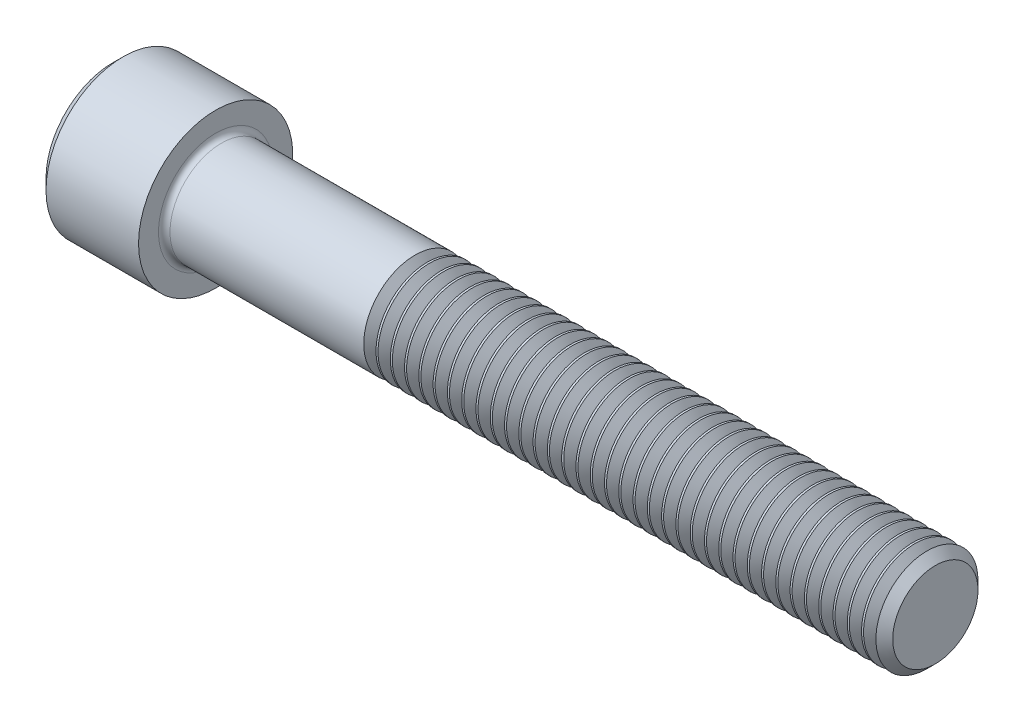
SolidWorks part; units mm, degrees
material "AISI 1020 Steel, Cold Rolled"
ref_plane "Front Plane" through (0, 0, 0) normal (0, 0, 1) x (1, 0, 0)
ref_plane "Top Plane" through (0, 0, 0) normal (0, 1, 0) x (1, 0, 0)
ref_plane "Right Plane" through (0, 0, 0) normal (1, 0, 0) x (0, 0, -1)
ref_plane "Plane1" through (0, 0, 0) normal (0, 0, -1) x (-1, 0, 0)
sketch "Sketch1" plane through (0, 0, 0) normal (0, 0, -1) x (-1, 0, 0)
  line L0 (-6.35, 4.7625) -> (-6.35, 0)
  line L1 (-6.35, 0) -> (0, 0)
  line L2 (0, 0) -> (0, 4.7625)
  line L3 (0, 4.7625) -> (-6.35, 4.7625)
  line L4 (-6.35, 0) -> (0, 0) construction
revolve "Revolve1" add sketch "Sketch1" angle 360 about L4
sketch "Sketch2" plane through (6.35, 0, 0) normal (1, 0, 0) x (0, 0, -1)
  circle A0 centre (0, 0) radius 3.175
extrude "Boss-Extrude1" add sketch "Sketch2" along normal blind 12.3212
sketch "Sketch3" plane through (18.6712, 0, 0) normal (1, 0, 0) x (0, 0, -1)
  circle A0 centre (0, 0) radius 3.175
extrude "Boss-Extrude2" add sketch "Sketch3" along normal blind 0.3788 draft 55
sketch "Sketch4" plane through (19.05, 0, 0) normal (1, 0, 0) x (0, 0, -1)
  circle A0 centre (0, 0) radius 2.634
extrude "Boss-Extrude3" add sketch "Sketch4" along normal blind 0.3788 draft 55 draft outward yes
sketch "Sketch5" plane through (19.4288, 0, 0) normal (1, 0, 0) x (0, 0, -1)
  circle A0 centre (0, 0) radius 3.175
extrude "Boss-Extrude4" add sketch "Sketch5" along normal blind 0.1243
sketch "Sketch6" plane through (19.5531, 0, 0) normal (1, 0, 0) x (0, 0, -1)
  circle A0 centre (0, 0) radius 3.175
extrude "Boss-Extrude5" add sketch "Sketch6" along normal blind 0.3788 draft 55
sketch "Sketch7" plane through (19.9319, 0, 0) normal (1, 0, 0) x (0, 0, -1)
  circle A0 centre (0, 0) radius 2.634
extrude "Boss-Extrude6" add sketch "Sketch7" along normal blind 0.3788 draft 55 draft outward yes
sketch "Sketch8" plane through (20.3108, 0, 0) normal (1, 0, 0) x (0, 0, -1)
  circle A0 centre (0, 0) radius 3.175
extrude "Boss-Extrude7" add sketch "Sketch8" along normal blind 0.1243
sketch "Sketch9" plane through (20.4351, 0, 0) normal (1, 0, 0) x (0, 0, -1)
  circle A0 centre (0, 0) radius 3.175
extrude "Boss-Extrude8" add sketch "Sketch9" along normal blind 0.3788 draft 55
sketch "Sketch10" plane through (20.8139, 0, 0) normal (1, 0, 0) x (0, 0, -1)
  circle A0 centre (0, 0) radius 2.634
extrude "Boss-Extrude9" add sketch "Sketch10" along normal blind 0.3788 draft 55 draft outward yes
sketch "Sketch11" plane through (21.1927, 0, 0) normal (1, 0, 0) x (0, 0, -1)
  circle A0 centre (0, 0) radius 3.175
extrude "Boss-Extrude10" add sketch "Sketch11" along normal blind 0.1243
sketch "Sketch12" plane through (21.317, 0, 0) normal (1, 0, 0) x (0, 0, -1)
  circle A0 centre (0, 0) radius 3.175
extrude "Boss-Extrude11" add sketch "Sketch12" along normal blind 0.3788 draft 55
sketch "Sketch13" plane through (21.6958, 0, 0) normal (1, 0, 0) x (0, 0, -1)
  circle A0 centre (0, 0) radius 2.634
extrude "Boss-Extrude12" add sketch "Sketch13" along normal blind 0.3788 draft 55 draft outward yes
sketch "Sketch14" plane through (22.0747, 0, 0) normal (1, 0, 0) x (0, 0, -1)
  circle A0 centre (0, 0) radius 3.175
extrude "Boss-Extrude13" add sketch "Sketch14" along normal blind 0.1243
sketch "Sketch15" plane through (22.199, 0, 0) normal (1, 0, 0) x (0, 0, -1)
  circle A0 centre (0, 0) radius 3.175
extrude "Boss-Extrude14" add sketch "Sketch15" along normal blind 0.3788 draft 55
sketch "Sketch16" plane through (22.5778, 0, 0) normal (1, 0, 0) x (0, 0, -1)
  circle A0 centre (0, 0) radius 2.634
extrude "Boss-Extrude15" add sketch "Sketch16" along normal blind 0.3788 draft 55 draft outward yes
sketch "Sketch17" plane through (22.9566, 0, 0) normal (1, 0, 0) x (0, 0, -1)
  circle A0 centre (0, 0) radius 3.175
extrude "Boss-Extrude16" add sketch "Sketch17" along normal blind 0.1243
sketch "Sketch18" plane through (23.0809, 0, 0) normal (1, 0, 0) x (0, 0, -1)
  circle A0 centre (0, 0) radius 3.175
extrude "Boss-Extrude17" add sketch "Sketch18" along normal blind 0.3788 draft 55
sketch "Sketch19" plane through (23.4597, 0, 0) normal (1, 0, 0) x (0, 0, -1)
  circle A0 centre (0, 0) radius 2.634
extrude "Boss-Extrude18" add sketch "Sketch19" along normal blind 0.3788 draft 55 draft outward yes
sketch "Sketch20" plane through (23.8385, 0, 0) normal (1, 0, 0) x (0, 0, -1)
  circle A0 centre (0, 0) radius 3.175
extrude "Boss-Extrude19" add sketch "Sketch20" along normal blind 0.1243
sketch "Sketch21" plane through (23.9628, 0, 0) normal (1, 0, 0) x (0, 0, -1)
  circle A0 centre (0, 0) radius 3.175
extrude "Boss-Extrude20" add sketch "Sketch21" along normal blind 0.3788 draft 55
sketch "Sketch22" plane through (24.3417, 0, 0) normal (1, 0, 0) x (0, 0, -1)
  circle A0 centre (0, 0) radius 2.634
extrude "Boss-Extrude21" add sketch "Sketch22" along normal blind 0.3788 draft 55 draft outward yes
sketch "Sketch23" plane through (24.7205, 0, 0) normal (1, 0, 0) x (0, 0, -1)
  circle A0 centre (0, 0) radius 3.175
extrude "Boss-Extrude22" add sketch "Sketch23" along normal blind 0.1243
sketch "Sketch24" plane through (24.8448, 0, 0) normal (1, 0, 0) x (0, 0, -1)
  circle A0 centre (0, 0) radius 3.175
extrude "Boss-Extrude23" add sketch "Sketch24" along normal blind 0.3788 draft 55
sketch "Sketch25" plane through (25.2236, 0, 0) normal (1, 0, 0) x (0, 0, -1)
  circle A0 centre (0, 0) radius 2.634
extrude "Boss-Extrude24" add sketch "Sketch25" along normal blind 0.3788 draft 55 draft outward yes
sketch "Sketch26" plane through (25.6024, 0, 0) normal (1, 0, 0) x (0, 0, -1)
  circle A0 centre (0, 0) radius 3.175
extrude "Boss-Extrude25" add sketch "Sketch26" along normal blind 0.1243
sketch "Sketch27" plane through (25.7267, 0, 0) normal (1, 0, 0) x (0, 0, -1)
  circle A0 centre (0, 0) radius 3.175
extrude "Boss-Extrude26" add sketch "Sketch27" along normal blind 0.3788 draft 55
sketch "Sketch28" plane through (26.1056, 0, 0) normal (1, 0, 0) x (0, 0, -1)
  circle A0 centre (0, 0) radius 2.634
extrude "Boss-Extrude27" add sketch "Sketch28" along normal blind 0.3788 draft 55 draft outward yes
sketch "Sketch29" plane through (26.4844, 0, 0) normal (1, 0, 0) x (0, 0, -1)
  circle A0 centre (0, 0) radius 3.175
extrude "Boss-Extrude28" add sketch "Sketch29" along normal blind 0.1243
sketch "Sketch30" plane through (26.6087, 0, 0) normal (1, 0, 0) x (0, 0, -1)
  circle A0 centre (0, 0) radius 3.175
extrude "Boss-Extrude29" add sketch "Sketch30" along normal blind 0.3788 draft 55
sketch "Sketch31" plane through (26.9875, 0, 0) normal (1, 0, 0) x (0, 0, -1)
  circle A0 centre (0, 0) radius 2.634
extrude "Boss-Extrude30" add sketch "Sketch31" along normal blind 0.3788 draft 55 draft outward yes
sketch "Sketch32" plane through (27.3663, 0, 0) normal (1, 0, 0) x (0, 0, -1)
  circle A0 centre (0, 0) radius 3.175
extrude "Boss-Extrude31" add sketch "Sketch32" along normal blind 0.1243
sketch "Sketch33" plane through (27.4906, 0, 0) normal (1, 0, 0) x (0, 0, -1)
  circle A0 centre (0, 0) radius 3.175
extrude "Boss-Extrude32" add sketch "Sketch33" along normal blind 0.3788 draft 55
sketch "Sketch34" plane through (27.8694, 0, 0) normal (1, 0, 0) x (0, 0, -1)
  circle A0 centre (0, 0) radius 2.634
extrude "Boss-Extrude33" add sketch "Sketch34" along normal blind 0.3788 draft 55 draft outward yes
sketch "Sketch35" plane through (28.2483, 0, 0) normal (1, 0, 0) x (0, 0, -1)
  circle A0 centre (0, 0) radius 3.175
extrude "Boss-Extrude34" add sketch "Sketch35" along normal blind 0.1243
sketch "Sketch36" plane through (28.3726, 0, 0) normal (1, 0, 0) x (0, 0, -1)
  circle A0 centre (0, 0) radius 3.175
extrude "Boss-Extrude35" add sketch "Sketch36" along normal blind 0.3788 draft 55
sketch "Sketch37" plane through (28.7514, 0, 0) normal (1, 0, 0) x (0, 0, -1)
  circle A0 centre (0, 0) radius 2.634
extrude "Boss-Extrude36" add sketch "Sketch37" along normal blind 0.3788 draft 55 draft outward yes
sketch "Sketch38" plane through (29.1302, 0, 0) normal (1, 0, 0) x (0, 0, -1)
  circle A0 centre (0, 0) radius 3.175
extrude "Boss-Extrude37" add sketch "Sketch38" along normal blind 0.1243
sketch "Sketch39" plane through (29.2545, 0, 0) normal (1, 0, 0) x (0, 0, -1)
  circle A0 centre (0, 0) radius 3.175
extrude "Boss-Extrude38" add sketch "Sketch39" along normal blind 0.3788 draft 55
sketch "Sketch40" plane through (29.6333, 0, 0) normal (1, 0, 0) x (0, 0, -1)
  circle A0 centre (0, 0) radius 2.634
extrude "Boss-Extrude39" add sketch "Sketch40" along normal blind 0.3788 draft 55 draft outward yes
sketch "Sketch41" plane through (30.0122, 0, 0) normal (1, 0, 0) x (0, 0, -1)
  circle A0 centre (0, 0) radius 3.175
extrude "Boss-Extrude40" add sketch "Sketch41" along normal blind 0.1243
sketch "Sketch42" plane through (30.1365, 0, 0) normal (1, 0, 0) x (0, 0, -1)
  circle A0 centre (0, 0) radius 3.175
extrude "Boss-Extrude41" add sketch "Sketch42" along normal blind 0.3788 draft 55
sketch "Sketch43" plane through (30.5153, 0, 0) normal (1, 0, 0) x (0, 0, -1)
  circle A0 centre (0, 0) radius 2.634
extrude "Boss-Extrude42" add sketch "Sketch43" along normal blind 0.3788 draft 55 draft outward yes
sketch "Sketch44" plane through (30.8941, 0, 0) normal (1, 0, 0) x (0, 0, -1)
  circle A0 centre (0, 0) radius 3.175
extrude "Boss-Extrude43" add sketch "Sketch44" along normal blind 0.1243
sketch "Sketch45" plane through (31.0184, 0, 0) normal (1, 0, 0) x (0, 0, -1)
  circle A0 centre (0, 0) radius 3.175
extrude "Boss-Extrude44" add sketch "Sketch45" along normal blind 0.3788 draft 55
sketch "Sketch46" plane through (31.3972, 0, 0) normal (1, 0, 0) x (0, 0, -1)
  circle A0 centre (0, 0) radius 2.634
extrude "Boss-Extrude45" add sketch "Sketch46" along normal blind 0.3788 draft 55 draft outward yes
sketch "Sketch47" plane through (31.776, 0, 0) normal (1, 0, 0) x (0, 0, -1)
  circle A0 centre (0, 0) radius 3.175
extrude "Boss-Extrude46" add sketch "Sketch47" along normal blind 0.1243
sketch "Sketch48" plane through (31.9003, 0, 0) normal (1, 0, 0) x (0, 0, -1)
  circle A0 centre (0, 0) radius 3.175
extrude "Boss-Extrude47" add sketch "Sketch48" along normal blind 0.3788 draft 55
sketch "Sketch49" plane through (32.2792, 0, 0) normal (1, 0, 0) x (0, 0, -1)
  circle A0 centre (0, 0) radius 2.634
extrude "Boss-Extrude48" add sketch "Sketch49" along normal blind 0.3788 draft 55 draft outward yes
sketch "Sketch50" plane through (32.658, 0, 0) normal (1, 0, 0) x (0, 0, -1)
  circle A0 centre (0, 0) radius 3.175
extrude "Boss-Extrude49" add sketch "Sketch50" along normal blind 0.1243
sketch "Sketch51" plane through (32.7823, 0, 0) normal (1, 0, 0) x (0, 0, -1)
  circle A0 centre (0, 0) radius 3.175
extrude "Boss-Extrude50" add sketch "Sketch51" along normal blind 0.3788 draft 55
sketch "Sketch52" plane through (33.1611, 0, 0) normal (1, 0, 0) x (0, 0, -1)
  circle A0 centre (0, 0) radius 2.634
extrude "Boss-Extrude51" add sketch "Sketch52" along normal blind 0.3788 draft 55 draft outward yes
sketch "Sketch53" plane through (33.5399, 0, 0) normal (1, 0, 0) x (0, 0, -1)
  circle A0 centre (0, 0) radius 3.175
extrude "Boss-Extrude52" add sketch "Sketch53" along normal blind 0.1243
sketch "Sketch54" plane through (33.6642, 0, 0) normal (1, 0, 0) x (0, 0, -1)
  circle A0 centre (0, 0) radius 3.175
extrude "Boss-Extrude53" add sketch "Sketch54" along normal blind 0.3788 draft 55
sketch "Sketch55" plane through (34.0431, 0, 0) normal (1, 0, 0) x (0, 0, -1)
  circle A0 centre (0, 0) radius 2.634
extrude "Boss-Extrude54" add sketch "Sketch55" along normal blind 0.3788 draft 55 draft outward yes
sketch "Sketch56" plane through (34.4219, 0, 0) normal (1, 0, 0) x (0, 0, -1)
  circle A0 centre (0, 0) radius 3.175
extrude "Boss-Extrude55" add sketch "Sketch56" along normal blind 0.1243
sketch "Sketch57" plane through (34.5462, 0, 0) normal (1, 0, 0) x (0, 0, -1)
  circle A0 centre (0, 0) radius 3.175
extrude "Boss-Extrude56" add sketch "Sketch57" along normal blind 0.3788 draft 55
sketch "Sketch58" plane through (34.925, 0, 0) normal (1, 0, 0) x (0, 0, -1)
  circle A0 centre (0, 0) radius 2.634
extrude "Boss-Extrude57" add sketch "Sketch58" along normal blind 0.3788 draft 55 draft outward yes
sketch "Sketch59" plane through (35.3038, 0, 0) normal (1, 0, 0) x (0, 0, -1)
  circle A0 centre (0, 0) radius 3.175
extrude "Boss-Extrude58" add sketch "Sketch59" along normal blind 0.1243
sketch "Sketch60" plane through (35.4281, 0, 0) normal (1, 0, 0) x (0, 0, -1)
  circle A0 centre (0, 0) radius 3.175
extrude "Boss-Extrude59" add sketch "Sketch60" along normal blind 0.3788 draft 55
sketch "Sketch61" plane through (35.8069, 0, 0) normal (1, 0, 0) x (0, 0, -1)
  circle A0 centre (0, 0) radius 2.634
extrude "Boss-Extrude60" add sketch "Sketch61" along normal blind 0.3788 draft 55 draft outward yes
sketch "Sketch62" plane through (36.1858, 0, 0) normal (1, 0, 0) x (0, 0, -1)
  circle A0 centre (0, 0) radius 3.175
extrude "Boss-Extrude61" add sketch "Sketch62" along normal blind 0.1243
sketch "Sketch63" plane through (36.3101, 0, 0) normal (1, 0, 0) x (0, 0, -1)
  circle A0 centre (0, 0) radius 3.175
extrude "Boss-Extrude62" add sketch "Sketch63" along normal blind 0.3788 draft 55
sketch "Sketch64" plane through (36.6889, 0, 0) normal (1, 0, 0) x (0, 0, -1)
  circle A0 centre (0, 0) radius 2.634
extrude "Boss-Extrude63" add sketch "Sketch64" along normal blind 0.3788 draft 55 draft outward yes
sketch "Sketch65" plane through (37.0677, 0, 0) normal (1, 0, 0) x (0, 0, -1)
  circle A0 centre (0, 0) radius 3.175
extrude "Boss-Extrude64" add sketch "Sketch65" along normal blind 0.1243
sketch "Sketch66" plane through (37.192, 0, 0) normal (1, 0, 0) x (0, 0, -1)
  circle A0 centre (0, 0) radius 3.175
extrude "Boss-Extrude65" add sketch "Sketch66" along normal blind 0.3788 draft 55
sketch "Sketch67" plane through (37.5708, 0, 0) normal (1, 0, 0) x (0, 0, -1)
  circle A0 centre (0, 0) radius 2.634
extrude "Boss-Extrude66" add sketch "Sketch67" along normal blind 0.3788 draft 55 draft outward yes
sketch "Sketch68" plane through (37.9497, 0, 0) normal (1, 0, 0) x (0, 0, -1)
  circle A0 centre (0, 0) radius 3.175
extrude "Boss-Extrude67" add sketch "Sketch68" along normal blind 0.1243
sketch "Sketch69" plane through (38.074, 0, 0) normal (1, 0, 0) x (0, 0, -1)
  circle A0 centre (0, 0) radius 3.175
extrude "Boss-Extrude68" add sketch "Sketch69" along normal blind 0.3788 draft 55
sketch "Sketch70" plane through (38.4528, 0, 0) normal (1, 0, 0) x (0, 0, -1)
  circle A0 centre (0, 0) radius 2.634
extrude "Boss-Extrude69" add sketch "Sketch70" along normal blind 0.3788 draft 55 draft outward yes
sketch "Sketch71" plane through (38.8316, 0, 0) normal (1, 0, 0) x (0, 0, -1)
  circle A0 centre (0, 0) radius 3.175
extrude "Boss-Extrude70" add sketch "Sketch71" along normal blind 0.1243
sketch "Sketch72" plane through (38.9559, 0, 0) normal (1, 0, 0) x (0, 0, -1)
  circle A0 centre (0, 0) radius 3.175
extrude "Boss-Extrude71" add sketch "Sketch72" along normal blind 0.3788 draft 55
sketch "Sketch73" plane through (39.3347, 0, 0) normal (1, 0, 0) x (0, 0, -1)
  circle A0 centre (0, 0) radius 2.634
extrude "Boss-Extrude72" add sketch "Sketch73" along normal blind 0.3788 draft 55 draft outward yes
sketch "Sketch74" plane through (39.7135, 0, 0) normal (1, 0, 0) x (0, 0, -1)
  circle A0 centre (0, 0) radius 3.175
extrude "Boss-Extrude73" add sketch "Sketch74" along normal blind 0.1243
sketch "Sketch75" plane through (39.8378, 0, 0) normal (1, 0, 0) x (0, 0, -1)
  circle A0 centre (0, 0) radius 3.175
extrude "Boss-Extrude74" add sketch "Sketch75" along normal blind 0.3788 draft 55
sketch "Sketch76" plane through (40.2167, 0, 0) normal (1, 0, 0) x (0, 0, -1)
  circle A0 centre (0, 0) radius 2.634
extrude "Boss-Extrude75" add sketch "Sketch76" along normal blind 0.3788 draft 55 draft outward yes
sketch "Sketch77" plane through (40.5955, 0, 0) normal (1, 0, 0) x (0, 0, -1)
  circle A0 centre (0, 0) radius 3.175
extrude "Boss-Extrude76" add sketch "Sketch77" along normal blind 0.1243
sketch "Sketch78" plane through (40.7198, 0, 0) normal (1, 0, 0) x (0, 0, -1)
  circle A0 centre (0, 0) radius 3.175
extrude "Boss-Extrude77" add sketch "Sketch78" along normal blind 0.3788 draft 55
sketch "Sketch79" plane through (41.0986, 0, 0) normal (1, 0, 0) x (0, 0, -1)
  circle A0 centre (0, 0) radius 2.634
extrude "Boss-Extrude78" add sketch "Sketch79" along normal blind 0.3788 draft 55 draft outward yes
sketch "Sketch80" plane through (41.4774, 0, 0) normal (1, 0, 0) x (0, 0, -1)
  circle A0 centre (0, 0) radius 3.175
extrude "Boss-Extrude79" add sketch "Sketch80" along normal blind 0.1243
sketch "Sketch81" plane through (41.6017, 0, 0) normal (1, 0, 0) x (0, 0, -1)
  circle A0 centre (0, 0) radius 3.175
extrude "Boss-Extrude80" add sketch "Sketch81" along normal blind 0.3788 draft 55
sketch "Sketch82" plane through (41.9806, 0, 0) normal (1, 0, 0) x (0, 0, -1)
  circle A0 centre (0, 0) radius 2.634
extrude "Boss-Extrude81" add sketch "Sketch82" along normal blind 0.3788 draft 55 draft outward yes
sketch "Sketch83" plane through (42.3594, 0, 0) normal (1, 0, 0) x (0, 0, -1)
  circle A0 centre (0, 0) radius 3.175
extrude "Boss-Extrude82" add sketch "Sketch83" along normal blind 0.1243
sketch "Sketch84" plane through (42.4837, 0, 0) normal (1, 0, 0) x (0, 0, -1)
  circle A0 centre (0, 0) radius 3.175
extrude "Boss-Extrude83" add sketch "Sketch84" along normal blind 0.3788 draft 55
sketch "Sketch85" plane through (42.8625, 0, 0) normal (1, 0, 0) x (0, 0, -1)
  circle A0 centre (0, 0) radius 2.634
extrude "Boss-Extrude84" add sketch "Sketch85" along normal blind 0.3788 draft 55 draft outward yes
sketch "Sketch86" plane through (43.2413, 0, 0) normal (1, 0, 0) x (0, 0, -1)
  circle A0 centre (0, 0) radius 3.175
extrude "Boss-Extrude85" add sketch "Sketch86" along normal blind 0.1243
sketch "Sketch87" plane through (43.3656, 0, 0) normal (1, 0, 0) x (0, 0, -1)
  circle A0 centre (0, 0) radius 3.175
extrude "Boss-Extrude86" add sketch "Sketch87" along normal blind 0.3788 draft 55
sketch "Sketch88" plane through (43.7444, 0, 0) normal (1, 0, 0) x (0, 0, -1)
  circle A0 centre (0, 0) radius 2.634
extrude "Boss-Extrude87" add sketch "Sketch88" along normal blind 0.3788 draft 55 draft outward yes
sketch "Sketch89" plane through (44.1233, 0, 0) normal (1, 0, 0) x (0, 0, -1)
  circle A0 centre (0, 0) radius 3.175
extrude "Boss-Extrude88" add sketch "Sketch89" along normal blind 0.1243
sketch "Sketch90" plane through (44.2476, 0, 0) normal (1, 0, 0) x (0, 0, -1)
  circle A0 centre (0, 0) radius 3.175
extrude "Boss-Extrude89" add sketch "Sketch90" along normal blind 0.3788 draft 55
sketch "Sketch91" plane through (44.6264, 0, 0) normal (1, 0, 0) x (0, 0, -1)
  circle A0 centre (0, 0) radius 2.634
extrude "Boss-Extrude90" add sketch "Sketch91" along normal blind 0.3788 draft 55 draft outward yes
sketch "Sketch92" plane through (45.0052, 0, 0) normal (1, 0, 0) x (0, 0, -1)
  circle A0 centre (0, 0) radius 3.175
extrude "Boss-Extrude91" add sketch "Sketch92" along normal blind 0.1243
sketch "Sketch93" plane through (45.1295, 0, 0) normal (1, 0, 0) x (0, 0, -1)
  circle A0 centre (0, 0) radius 3.175
extrude "Boss-Extrude92" add sketch "Sketch93" along normal blind 0.3788 draft 55
sketch "Sketch94" plane through (45.5083, 0, 0) normal (1, 0, 0) x (0, 0, -1)
  circle A0 centre (0, 0) radius 2.634
extrude "Boss-Extrude93" add sketch "Sketch94" along normal blind 0.3788 draft 55 draft outward yes
sketch "Sketch95" plane through (45.8872, 0, 0) normal (1, 0, 0) x (0, 0, -1)
  circle A0 centre (0, 0) radius 3.175
extrude "Boss-Extrude94" add sketch "Sketch95" along normal blind 0.1243
sketch "Sketch96" plane through (46.0115, 0, 0) normal (1, 0, 0) x (0, 0, -1)
  circle A0 centre (0, 0) radius 3.175
extrude "Boss-Extrude95" add sketch "Sketch96" along normal blind 0.3788 draft 55
sketch "Sketch97" plane through (46.3903, 0, 0) normal (1, 0, 0) x (0, 0, -1)
  circle A0 centre (0, 0) radius 2.634
extrude "Boss-Extrude96" add sketch "Sketch97" along normal blind 0.3788 draft 55 draft outward yes
sketch "Sketch98" plane through (46.7691, 0, 0) normal (1, 0, 0) x (0, 0, -1)
  circle A0 centre (0, 0) radius 3.175
extrude "Boss-Extrude97" add sketch "Sketch98" along normal blind 0.1243
sketch "Sketch99" plane through (46.8934, 0, 0) normal (1, 0, 0) x (0, 0, -1)
  circle A0 centre (0, 0) radius 3.175
extrude "Boss-Extrude98" add sketch "Sketch99" along normal blind 0.3788 draft 55
sketch "Sketch100" plane through (47.2722, 0, 0) normal (1, 0, 0) x (0, 0, -1)
  circle A0 centre (0, 0) radius 2.634
extrude "Boss-Extrude99" add sketch "Sketch100" along normal blind 0.3788 draft 55 draft outward yes
sketch "Sketch101" plane through (47.651, 0, 0) normal (1, 0, 0) x (0, 0, -1)
  circle A0 centre (0, 0) radius 3.175
extrude "Boss-Extrude100" add sketch "Sketch101" along normal blind 0.1243
sketch "Sketch102" plane through (47.7753, 0, 0) normal (1, 0, 0) x (0, 0, -1)
  circle A0 centre (0, 0) radius 3.175
extrude "Boss-Extrude101" add sketch "Sketch102" along normal blind 0.3788 draft 55
sketch "Sketch103" plane through (48.1542, 0, 0) normal (1, 0, 0) x (0, 0, -1)
  circle A0 centre (0, 0) radius 2.634
extrude "Boss-Extrude102" add sketch "Sketch103" along normal blind 0.3788 draft 55 draft outward yes
sketch "Sketch104" plane through (48.533, 0, 0) normal (1, 0, 0) x (0, 0, -1)
  circle A0 centre (0, 0) radius 3.175
extrude "Boss-Extrude103" add sketch "Sketch104" along normal blind 0.1243
sketch "Sketch105" plane through (48.6573, 0, 0) normal (1, 0, 0) x (0, 0, -1)
  circle A0 centre (0, 0) radius 3.175
extrude "Boss-Extrude104" add sketch "Sketch105" along normal blind 0.3788 draft 55
sketch "Sketch106" plane through (49.0361, 0, 0) normal (1, 0, 0) x (0, 0, -1)
  circle A0 centre (0, 0) radius 2.634
extrude "Boss-Extrude105" add sketch "Sketch106" along normal blind 0.3788 draft 55 draft outward yes
sketch "Sketch107" plane through (49.4149, 0, 0) normal (1, 0, 0) x (0, 0, -1)
  circle A0 centre (0, 0) radius 3.175
extrude "Boss-Extrude106" add sketch "Sketch107" along normal blind 0.1243
sketch "Sketch108" plane through (49.5392, 0, 0) normal (1, 0, 0) x (0, 0, -1)
  circle A0 centre (0, 0) radius 3.175
extrude "Boss-Extrude107" add sketch "Sketch108" along normal blind 0.3788 draft 55
sketch "Sketch109" plane through (49.9181, 0, 0) normal (1, 0, 0) x (0, 0, -1)
  circle A0 centre (0, 0) radius 2.634
extrude "Boss-Extrude108" add sketch "Sketch109" along normal blind 0.3632 draft 55 draft outward yes
sketch "Sketch110" plane through (50.2813, 0, 0) normal (1, 0, 0) x (0, 0, -1)
  circle A0 centre (0, 0) radius 3.1527
extrude "Boss-Extrude109" add sketch "Sketch110" along normal blind 0.5187 draft 45
sketch "Sketch111" plane through (0, 0, 0) normal (-1, 0, 0) x (0, 0, 1)
  line L0 (-2.3813, -1.3748) -> (0, -2.7496)
  line L1 (0, -2.7496) -> (2.3812, -1.3748)
  line L2 (2.3812, -1.3748) -> (2.3812, 1.3748)
  line L3 (2.3812, 1.3748) -> (0, 2.7496)
  line L4 (0, 2.7496) -> (-2.3813, 1.3748)
  line L5 (-2.3813, 1.3748) -> (-2.3813, -1.3748)
extrude "Cut-Extrude1" cut sketch "Sketch111" against normal blind 3.048
sketch "Sketch112" plane through (0, 0, 0) normal (0, 0, 1) x (1, 0, 0)
  line L0 (3.048, 2.3813) -> (3.048, 0)
  line L1 (3.048, 0) -> (4.4228, 0)
  line L2 (4.4228, 0) -> (3.048, 2.3813)
  line L3 (3.048, 0) -> (4.4229, 0) construction
revolve "Cut-Revolve1" cut sketch "Sketch112" angle 360 about L3
chamfer "Chamfer1" distance 0.635 angle 45 1 edges at (0, 0, 4.7625)
fillet "Fillet1" radius 0.3556 1 edges at (6.35, 0, -3.175)
